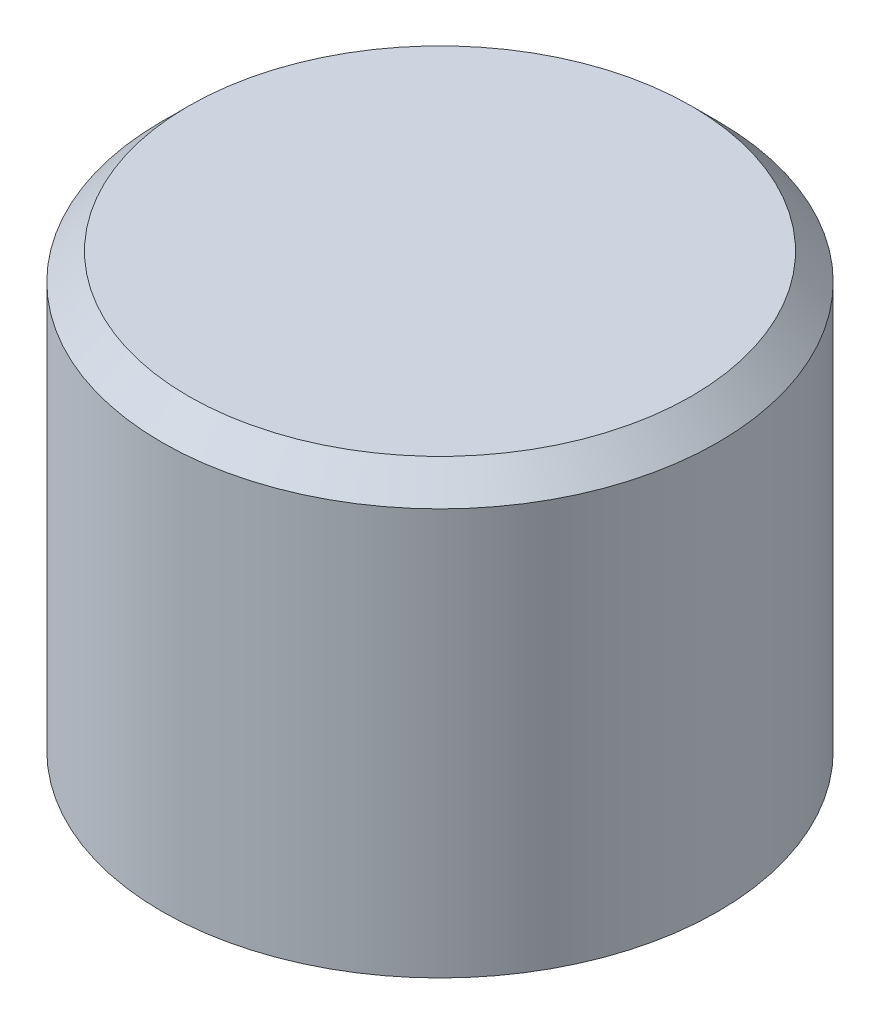
SolidWorks part; units mm, degrees
ref_plane "Спереди" through (0, 0, 0) normal (0, 0, 1) x (1, 0, 0)
ref_plane "Сверху" through (0, 0, 0) normal (0, 1, 0) x (1, 0, 0)
ref_plane "Справа" through (0, 0, 0) normal (1, 0, 0) x (0, 0, -1)
sketch "Эскиз1" plane through (0, 0, 0) normal (0, 0, 1) x (1, 0, 0)
  line L0 (0, 0) -> (-8.35, 0)
  line L1 (-8.35, 0) -> (-8.35, -13)
  line L2 (-8.35, -13) -> (-7.5, -13)
  line L3 (-7.5, -13) -> (-7.5, -10.7)
  line L4 (-7.5, -10.7) -> (-2.5, -10.7)
  line L5 (-2.5, -10.7) -> (-2.5, -3)
  line L6 (-2.5, -3) -> (0, -3)
  line L7 (0, -3) -> (0, 0)
  dimension "D1" = 8.35
  dimension "D2" = 13
  dimension "D3" = 2.5
  dimension "D4" = 2.3
  dimension "D5" = 7.5
  dimension "D6" = 10
revolve "Повернуть1" add sketch "Эскиз1" angle 360 about L7
chamfer "Фаска1" distance 0.8 angle 45 1 edges at (0, 0, -8.35)
